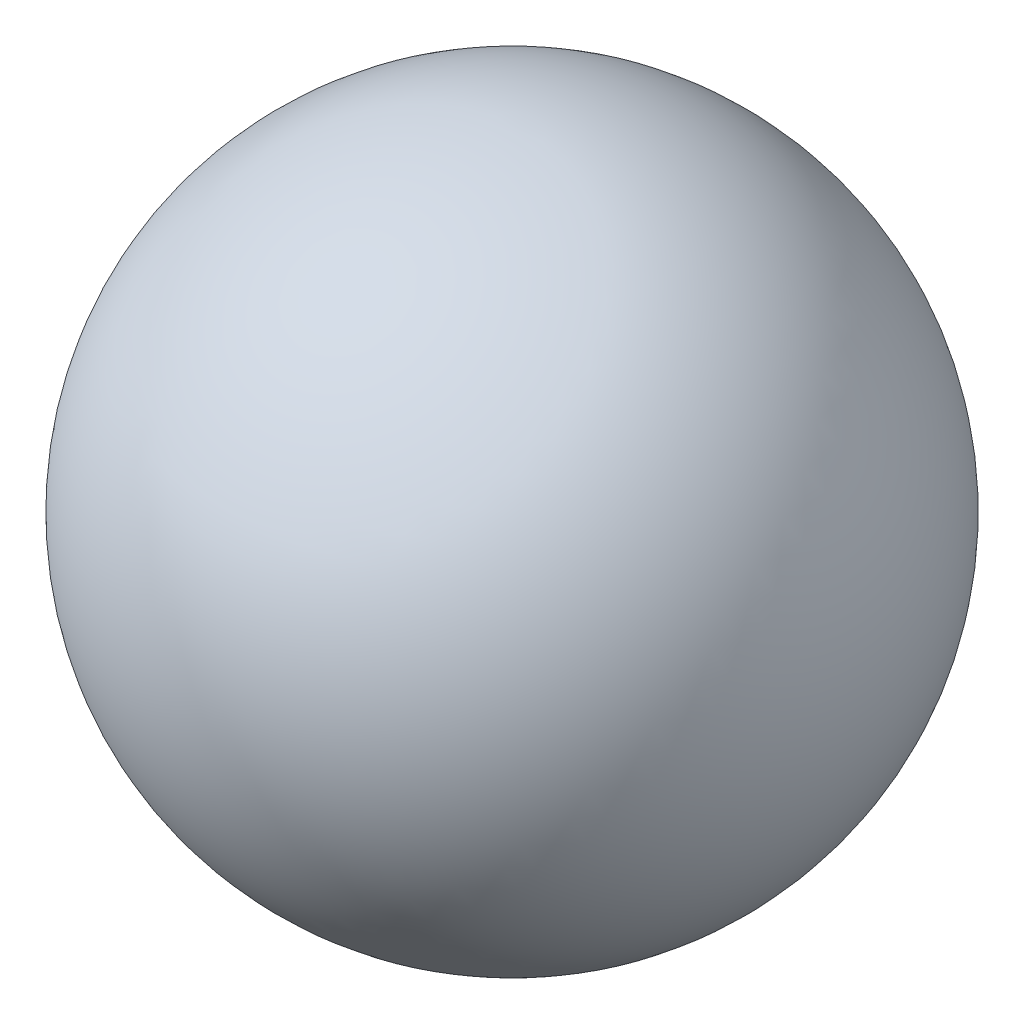
SolidWorks part; units mm, degrees
material "Alloy Steel"
ref_plane "Front Plane" through (0, 0, 0) normal (0, 0, 1) x (1, 0, 0)
ref_plane "Top Plane" through (0, 0, 0) normal (0, 1, 0) x (1, 0, 0)
ref_plane "Right Plane" through (0, 0, 0) normal (1, 0, 0) x (0, 0, -1)
sketch "Sketch1" plane through (0, 0, 0) normal (0, 0, 1) x (1, 0, 0)
  line L0 (0, 40.814) -> (0, -55.9302) construction
  line L1 (0, 25) -> (0, -25)
  arc A0 (0, -25) -> (0, 25) centre (0, 0) ccw
  dimension "D1" = 50
revolve "Revolve1" add sketch "Sketch1" angle 360 about L0
